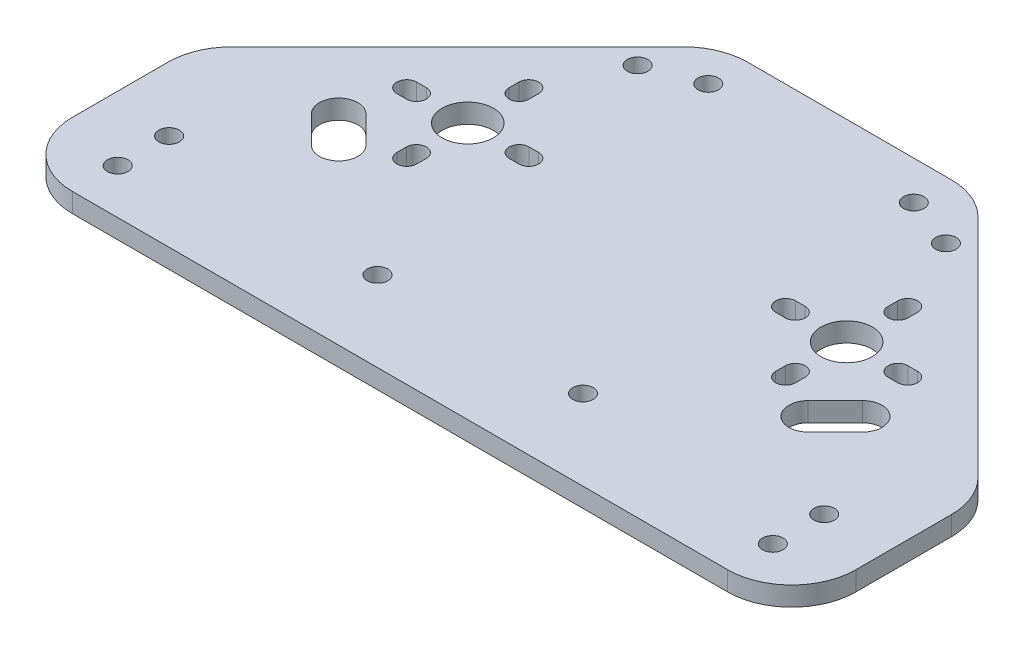
SolidWorks part; units mm, degrees
ref_plane "前视基准面" through (0, 0, 0) normal (0, 0, 1) x (1, 0, 0)
ref_plane "上视基准面" through (0, 0, 0) normal (0, 1, 0) x (1, 0, 0)
ref_plane "右视基准面" through (0, 0, 0) normal (1, 0, 0) x (0, 0, -1)
sketch "草图1" plane through (0, 0, 0) normal (0, 1, 0) x (1, 0, 0)
  line L0 (0, 30) -> (-15.8579, 30)
  line L1 (22.9289, 27.0711) -> (58.0711, -8.0711)
  line L3 (-36, -40) -> (36, -40)
  line L5 (0, 30) -> (15.8579, 30)
  line L7 (-36, -40) -> (-51, -40)
  line L8 (36, -40) -> (51, -40)
  line L9 (-22.9289, 27.0711) -> (-58.0711, -8.0711)
  line L10 (-61, -15.1421) -> (-61, -30)
  line L12 (61, -15.1421) -> (61, -30)
  arc A0 (-15.8579, 30) -> (-22.9289, 27.0711) centre (-15.8579, 20) ccw
  arc A1 (22.9289, 27.0711) -> (15.8579, 30) centre (15.8579, 20) ccw
  arc A2 (61, -15.1421) -> (58.0711, -8.0711) centre (51, -15.1421) ccw
  arc A3 (61, -30) -> (51, -40) centre (51, -30) cw
  arc A4 (-51, -40) -> (-61, -30) centre (-51, -30) cw
  arc A5 (-61, -15.1421) -> (-58.0711, -8.0711) centre (-51, -15.1421) cw
  point P0 (0, 0)
  dimension "D1" = 10
  dimension "D2" = 10
  dimension "D3" = 10
sketch "草图2" plane through (0, 0, 0) normal (0, 1, 0) x (1, 0, 0)
  line L0 (-37.4505, -1.55) -> (-38.9505, -1.55)
  line L1 (38.7282, -6.6787) -> (34.4856, -10.9213)
  line L2 (-37.4505, 1.55) -> (-38.9505, 1.55)
  line L3 (-31.0005, 8) -> (-31.0005, 9.5)
  line L4 (-27.9002, 8) -> (-27.9002, 9.5)
  line L5 (-27.9005, -8) -> (-27.9005, -9.5)
  line L6 (-31.0005, -8) -> (-31.0005, -9.5)
  line L7 (-21.4505, 1.55) -> (-19.9505, 1.55)
  line L8 (-21.4505, -1.55) -> (-19.9505, -1.55)
  line L9 (42.9708, -10.9213) -> (38.7282, -15.164)
  line L10 (21.5495, -1.55) -> (20.0495, -1.55)
  line L11 (21.5495, 1.55) -> (20.0495, 1.55)
  line L12 (-42.8718, -10.9213) -> (-38.6292, -15.164)
  line L13 (31.0995, -8) -> (31.0995, -9.5)
  line L14 (27.9995, -8) -> (27.9995, -9.5)
  line L15 (-38.6292, -6.6787) -> (-34.3865, -10.9213)
  line L16 (27.9995, 8) -> (27.9995, 9.5)
  line L17 (31.0995, 8) -> (31.0995, 9.5)
  line L18 (37.5495, 1.55) -> (39.0495, 1.55)
  line L19 (37.5495, -1.55) -> (39.0495, -1.55)
  circle A0 centre (-16, 24) radius 1.6
  circle A1 centre (16, 24) radius 1.6
  circle A2 centre (-24, 21) radius 1.6
  circle A3 centre (24, 21) radius 1.6
  circle A4 centre (-29.4505, 0) radius 4
  arc A5 (38.7282, -15.164) -> (34.4856, -10.9213) centre (36.6069, -13.0426) cw
  arc A6 (-31.0005, 8) -> (-27.9002, 8) centre (-29.4503, 8) ccw
  arc A7 (-27.9002, 9.5) -> (-31.0005, 9.5) centre (-29.4503, 9.5) ccw
  arc A8 (-37.4505, -1.55) -> (-37.4505, 1.55) centre (-37.4505, 0) ccw
  arc A9 (-38.9505, 1.55) -> (-38.9505, -1.55) centre (-38.9505, 0) ccw
  arc A10 (-27.9005, -8) -> (-31.0005, -8) centre (-29.4505, -8) ccw
  arc A11 (-31.0005, -9.5) -> (-27.9005, -9.5) centre (-29.4505, -9.5) ccw
  arc A12 (-21.4505, 1.55) -> (-21.4505, -1.55) centre (-21.4505, 0) ccw
  arc A13 (-19.9505, -1.55) -> (-19.9505, 1.55) centre (-19.9505, 0) ccw
  arc A14 (-38.6292, -6.6787) -> (-42.8718, -10.9213) centre (-40.7505, -8.8) ccw
  arc A15 (-38.6292, -15.164) -> (-34.3865, -10.9213) centre (-36.5078, -13.0426) ccw
  arc A16 (38.7282, -6.6787) -> (42.9708, -10.9213) centre (40.8495, -8.8) cw
  arc A17 (20.0495, -1.55) -> (20.0495, 1.55) centre (20.0495, 0) cw
  arc A18 (21.5495, 1.55) -> (21.5495, -1.55) centre (21.5495, 0) cw
  arc A19 (31.0995, -9.5) -> (27.9995, -9.5) centre (29.5495, -9.5) cw
  arc A20 (27.9995, -8) -> (31.0995, -8) centre (29.5495, -8) cw
  arc A21 (39.0495, 1.55) -> (39.0495, -1.55) centre (39.0495, 0) cw
  arc A22 (37.5495, -1.55) -> (37.5495, 1.55) centre (37.5495, 0) cw
  arc A23 (27.9995, 9.5) -> (31.0995, 9.5) centre (29.5495, 9.5) cw
  arc A24 (31.0995, 8) -> (27.9995, 8) centre (29.5495, 8) cw
  circle A25 centre (29.5495, 0) radius 4
  circle A26 centre (-50.9505, -25) radius 1.6
  circle A27 centre (-50.9505, -33) radius 1.6
  circle A28 centre (51.0495, -33) radius 1.6
  circle A29 centre (51.0495, -25) radius 1.6
  circle A30 centre (-16, -27.5) radius 1.6
  circle A31 centre (16, -27.5) radius 1.6
  point P35 (-29.4505, -29.5)
  point P43 (-29.4505, 0)
extrude "凸台-拉伸1" add sketch "草图1" along normal blind 3
extrude "切除-拉伸1" cut sketch "草图2" along normal blind 3
